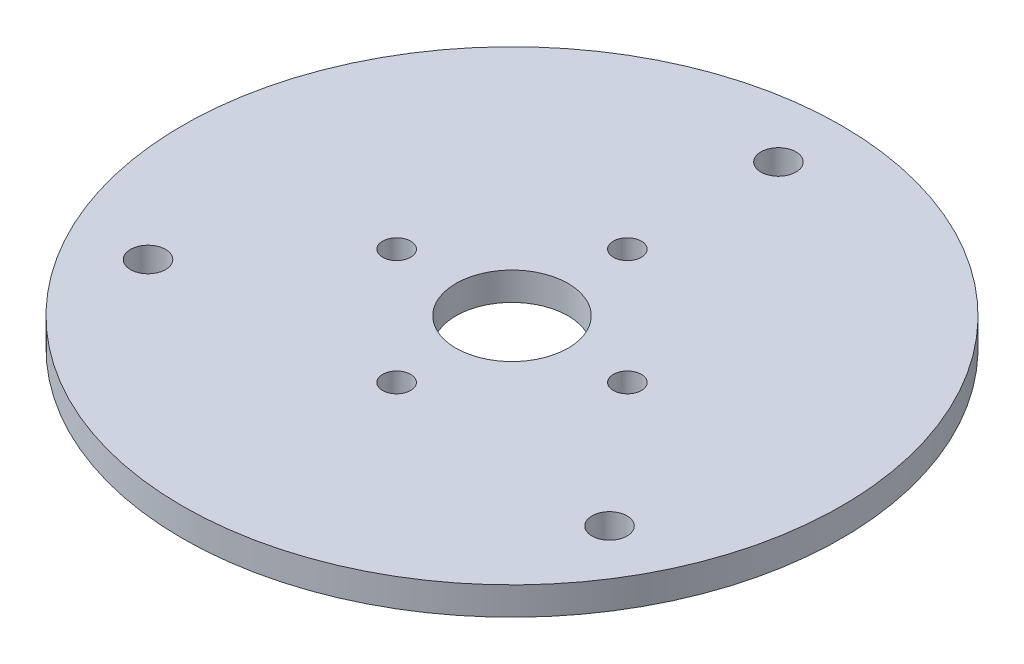
SolidWorks part; units mm, degrees
ref_plane "Front Plane" through (0, 0, 0) normal (0, 0, 1) x (1, 0, 0)
ref_plane "Top Plane" through (0, 0, 0) normal (0, 1, 0) x (1, 0, 0)
ref_plane "Right Plane" through (0, 0, 0) normal (1, 0, 0) x (0, 0, -1)
sketch "Sketch1" plane through (0, 0, 0) normal (0, 1, 0) x (1, 0, 0)
  circle A0 centre (0, 0) radius 23.5
  dimension "D1" = 47
extrude "Boss-Extrude1" add sketch "Sketch1" along normal blind 2 contours A0
sketch "Sketch2" plane through (0, 2, 0) normal (0, 1, 0) x (1, 0, 0)
  circle A2 centre (0, 8.2271) radius 1
  circle A3 centre (8.2271, 0) radius 1
  circle A4 centre (0, -8.2271) radius 1
  circle A5 centre (-8.2271, 0) radius 1
  circle A6 centre (0, 19) radius 1.25
  circle A8 centre (16.4545, -9.5) radius 1.25
  circle A9 centre (-16.4545, -9.5) radius 1.25
  dimension "D1" = 19
  dimension "D2" = 4
  dimension "D3" = 2.5
  dimension "D4" = 3
extrude "Cut-Extrude1" cut sketch "Sketch2" against normal through all
sketch "Sketch3" plane through (0, 0, 0) normal (0, -1, 0) x (1, 0, 0)
  circle A0 centre (0, 0) radius 4
  dimension "D1" = 8
extrude "Cut-Extrude2" cut sketch "Sketch3" against normal up to next
sketch "Sketch4" plane through (0, 0, 0) normal (0, -1, 0) x (1, 0, 0)
  circle A0 centre (-16.4545, 9.5) radius 3
  circle A1 centre (16.4545, 9.5) radius 3
  circle A2 centre (0, -19) radius 3
  dimension "D1" = 6
  dimension "D2" = 3
extrude "Cut-Extrude3" [suppressed] cut sketch "Sketch4" against normal blind 2.5
sketch "Sketch5" plane through (0, 2, 0) normal (0, 1, 0) x (1, 0, 0)
  circle A0 centre (8.2271, 0) radius 2
  circle A1 centre (0, -8.2271) radius 2
  circle A2 centre (-8.2271, 0) radius 2
  circle A3 centre (0, 8.2271) radius 2
  dimension "D1" = 4
  dimension "D2" = 4
extrude "Cut-Extrude4" [suppressed] cut sketch "Sketch5" against normal blind 1
